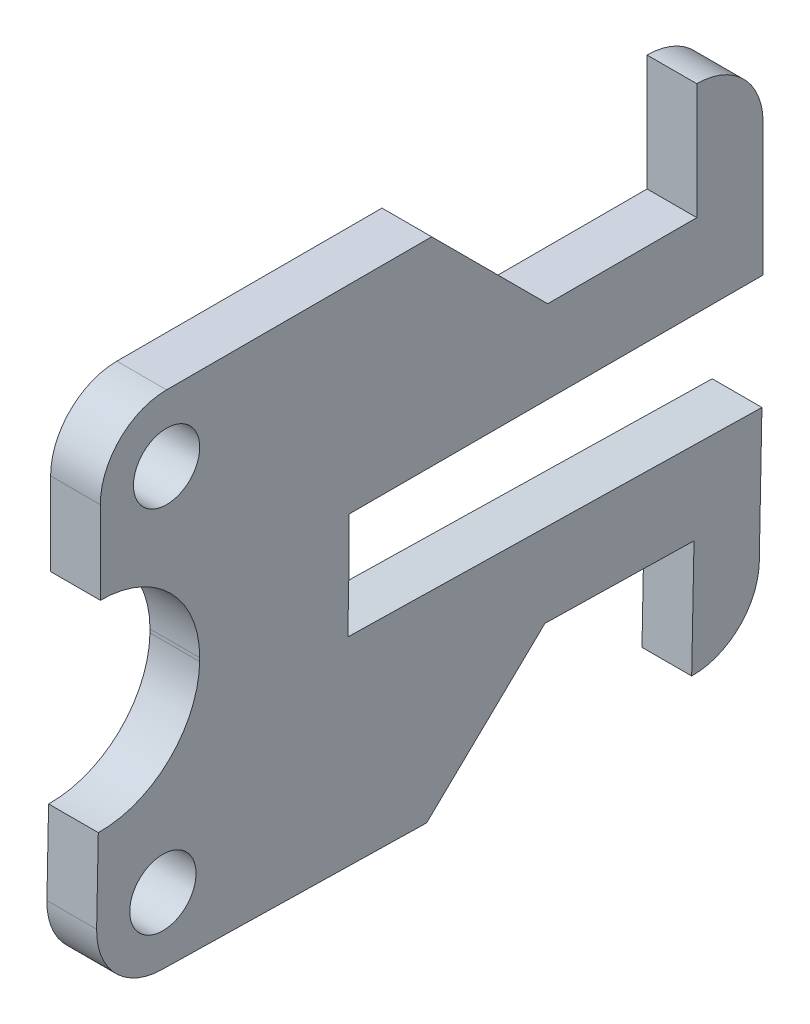
SolidWorks part; units mm, degrees
material "Copper"
ref_plane "Front Plane" through (0, 0, 0) normal (0, 0, 1) x (1, 0, 0)
ref_plane "Top Plane" through (0, 0, 0) normal (0, 1, 0) x (1, 0, 0)
ref_plane "Right Plane" through (0, 0, 0) normal (1, 0, 0) x (0, 0, -1)
sketch "Sketch1" plane through (0, 0, 0) normal (1, 0, 0) x (0, 0, -1)
  line L1 (0, 0) -> (0, 3)
  line L2 (0, 3) -> (25, 3)
  line L3 (25, 3) -> (25, 11)
  line L5 (21, 15) -> (21, 8)
  line L6 (21, 8) -> (12, 8)
  line L7 (12, 8) -> (5, 15)
  line L8 (5, 15) -> (-11, 15)
  line L9 (-15, 11) -> (-15, 6)
  line L10 (-19.1162, 0) -> (25, -0.4435) construction
  line L11 (-15.222, -11.0805) -> (-15.1214, -6.0815)
  line L12 (4.6936, -15.4818) -> (-11.3032, -15.1601)
  line L13 (11.8329, -8.6239) -> (4.6936, -15.4818)
  line L14 (20.8311, -8.8048) -> (11.8329, -8.6239)
  line L15 (20.6903, -15.8034) -> (20.8311, -8.8048)
  line L16 (24.9308, -3.8863) -> (24.77, -11.8846)
  line L17 (-0.0642, -3.3837) -> (24.9308, -3.8863)
  line L18 (-0.0039, -0.3843) -> (-0.0642, -3.3837)
  line L19 (-9, 0) -> (-9.002, -0.2034)
  line L20 (0, 0) -> (-0.0039, -0.3843)
  arc A0 (-15, 6) -> (-9, 0) centre (-15, 0) cw
  arc A1 (-11, 15) -> (-15, 11) centre (-11, 11) ccw
  arc A2 (21, 15) -> (25, 11) centre (21, 11) cw
  circle A3 centre (-11, 11) radius 2
  circle A4 centre (-11.2228, -11.1609) radius 2
  arc A5 (-15.1214, -6.0815) -> (-9.002, -0.2034) centre (-15.0008, -0.0827) ccw
  arc A6 (-11.3032, -15.1601) -> (-15.222, -11.0805) centre (-11.2228, -11.1609) cw
  arc A7 (20.6903, -15.8034) -> (24.77, -11.8846) centre (20.7708, -11.8042) ccw
  point P17 (-15, 15)
  dimension "D1" = 3
  dimension "D6" = 40
  dimension "D10" = 4
  dimension "D9" = 4
  dimension "D2" = 25
  dimension "D3" = 5
  dimension "D4" = 7
  dimension "D5" = 15
  dimension "D7" = 20
  dimension "D8" = 135
extrude "Boss-Extrude1" add sketch "Sketch1" along normal mid plane 3
